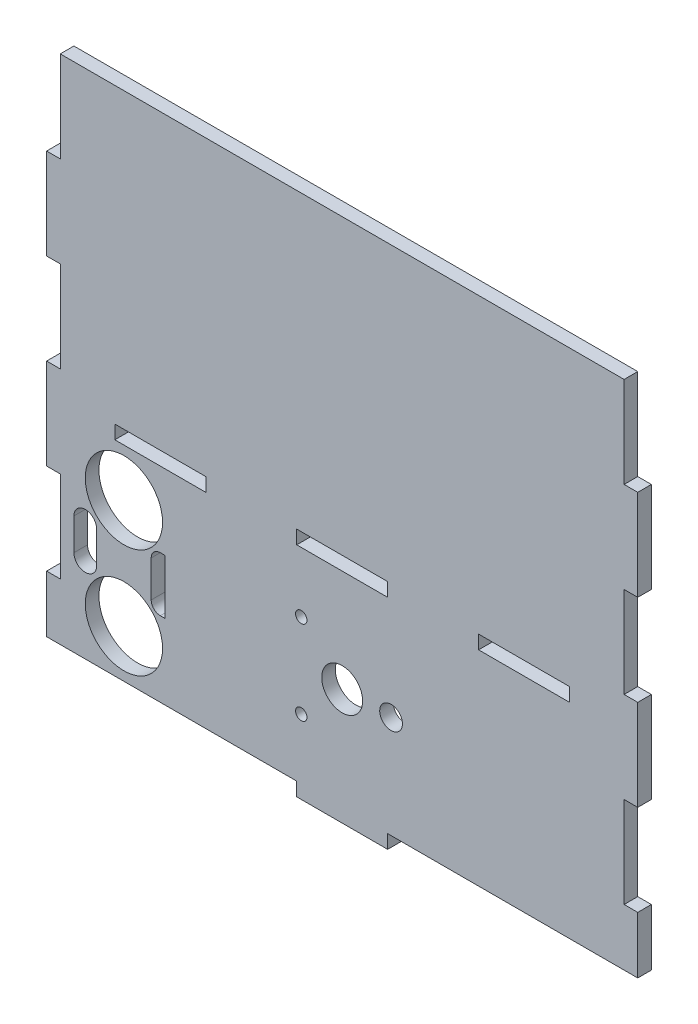
SolidWorks part; units mm, degrees
ref_plane "Front Plane" through (0, 0, 0) normal (0, 0, 1) x (1, 0, 0)
ref_plane "Top Plane" through (0, 0, 0) normal (0, 1, 0) x (1, 0, 0)
ref_plane "Right Plane" through (0, 0, 0) normal (1, 0, 0) x (0, 0, -1)
sketch "Sketch1" plane through (0, 0, 0) normal (0, 0, 1) x (1, 0, 0)
  line L0 (-10, -22.5) -> (-65, -22.5)
  line L1 (65, -22.5) -> (10, -22.5)
  line L2 (65, -22.5) -> (65, -10)
  line L4 (-65, -22.5) -> (-65, -10)
  line L5 (65, -22.5) -> (-65, 22.5) construction
  line L6 (65, 22.5) -> (-65, -22.5) construction
  line L8 (-10, -22.5) -> (-10, -25.5)
  line L9 (-10, -25.5) -> (10, -25.5)
  line L10 (10, -22.5) -> (10, -25.5)
  line L11 (0, -55) -> (0, 55) construction
  line L12 (-62, -10) -> (-65, -10)
  line L13 (-62, -10) -> (-62, 10)
  line L14 (-62, 10) -> (-65, 10)
  line L16 (-62, -10) -> (-65, 10) construction
  line L17 (-62, 10) -> (-65, -10) construction
  line L18 (62, 10) -> (65, 10)
  line L20 (62, -10) -> (65, -10)
  line L21 (62, -10) -> (62, 10)
  line L22 (-65, 10) -> (-65, 22.5)
  line L23 (65, 10) -> (65, 22.5)
  line L24 (-56.5, 3.5) -> (-56.5, -3.5) construction
  line L29 (-54, 3.5) -> (-54, -3.5)
  line L30 (-59, 3.5) -> (-59, -3.5)
  line L31 (-39, -6) -> (-40, -6)
  line L32 (-39, -6) -> (-39, 6)
  line L33 (-39, 6) -> (-40, 6)
  line L34 (-42, -4) -> (-42, 4)
  line L35 (-39, -6) -> (-42, 6) construction
  line L36 (-39, 6) -> (-42, -6) construction
  line L37 (55, 0) -> (-55, 0) construction
  line L40 (-65, 22.5) -> (-65, 30)
  line L41 (-62, 90) -> (62, 90)
  line L42 (65, 22.5) -> (65, 30)
  line L43 (30, 25.5) -> (50, 25.5)
  line L56 (-10, 22.5) -> (10, 22.5)
  line L57 (-10, 22.5) -> (-10, 25.5)
  line L58 (-10, 25.5) -> (10, 25.5)
  line L59 (10, 22.5) -> (10, 25.5)
  line L60 (-10, 22.5) -> (10, 25.5) construction
  line L61 (-10, 25.5) -> (10, 22.5) construction
  line L62 (-30, 22.5) -> (-50, 22.5)
  line L63 (-30, 22.5) -> (-30, 25.5)
  line L64 (-30, 25.5) -> (-50, 25.5)
  line L65 (-50, 22.5) -> (-50, 25.5)
  line L66 (-30, 22.5) -> (-50, 25.5) construction
  line L67 (-30, 25.5) -> (-50, 22.5) construction
  line L68 (50, 22.5) -> (50, 25.5)
  line L69 (30, 22.5) -> (50, 22.5)
  line L70 (30, 22.5) -> (30, 25.5)
  line L71 (62, 50) -> (65, 50)
  line L72 (-62, 30) -> (-65, 30)
  line L73 (-62, 30) -> (-62, 50)
  line L74 (-62, 50) -> (-65, 50)
  line L76 (-62, 30) -> (-65, 50) construction
  line L77 (-62, 50) -> (-65, 30) construction
  line L82 (65, 70) -> (62, 70)
  line L85 (62, 30) -> (65, 30)
  line L86 (62, 30) -> (62, 50)
  line L92 (-65, 70) -> (-62, 70)
  line L93 (-62, 90) -> (-62, 70)
  line L94 (62, 90) -> (62, 70)
  line L97 (-65, 50) -> (-65, 70)
  line L98 (65, 50) -> (65, 70)
  circle A0 centre (-48, 12) radius 8.5
  circle A1 centre (-48, -12) radius 8.5
  circle A6 centre (0, 0) radius 4.5
  circle A7 centre (10.75, 0) radius 2.5
  arc A10 (-54, 3.5) -> (-59, 3.5) centre (-56.5, 3.5) ccw
  arc A11 (-59, -3.5) -> (-54, -3.5) centre (-56.5, -3.5) ccw
  arc A12 (-40, -6) -> (-42, -4) centre (-40, -4) cw
  arc A13 (-40, 6) -> (-42, 4) centre (-40, 4) ccw
  circle A14 centre (-9, 9.25) radius 1.25
  circle A15 centre (-9, -9.25) radius 1.25
  point P0 (0, 0)
  point P10 (-63.5, 0)
  point P26 (-56.5, 0)
  point P49 (-40.5, 0)
  point P55 (0, 24)
  point P61 (-40, 24)
  point P69 (-63.5, 40)
  dimension "D8" = 17
  dimension "D15" = 2
  dimension "D16" = 9
  dimension "D17" = 5
  dimension "D22" = 2.5
  dimension "D12" = 2.5
  dimension "D1" = 130
  dimension "D2" = 45
  dimension "D3" = 3
  dimension "D4" = 20
  dimension "D5" = 55
  dimension "D6" = 20
  dimension "D7" = 3
  dimension "D9" = 17
  dimension "D10" = 24
  dimension "D11" = 12
  dimension "D13" = 7
  dimension "D14" = 6
  dimension "D18" = 10.75
  dimension "D19" = 3
  dimension "D20" = 12
  dimension "D21" = 6
  dimension "D23" = 9
  dimension "D24" = 9.25
  dimension "D25" = 67.5
  dimension "D26" = 20
  dimension "D27" = 3
  dimension "D28" = 45
  dimension "D29" = 20
  dimension "D30" = 3
  dimension "D31" = 20
  dimension "D32" = 20
  dimension "D33" = 20
  dimension "D34" = 3
  dimension "D35" = 3
  dimension "D36" = 20
extrude "Boss-Extrude1" add sketch "Sketch1" along normal blind 3
